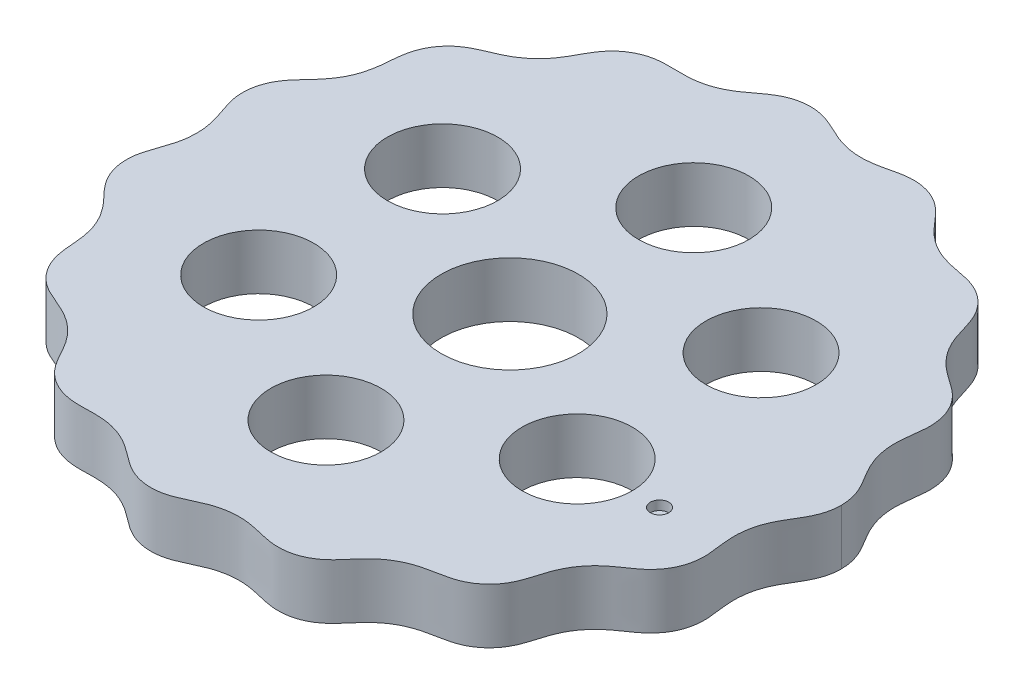
SolidWorks part; units mm, degrees
ref_plane "Front Plane" through (0, 0, 0) normal (0, 0, 1) x (1, 0, 0)
ref_plane "Top Plane" through (0, 0, 0) normal (0, 1, 0) x (1, 0, 0)
ref_plane "Right Plane" through (0, 0, 0) normal (1, 0, 0) x (0, 0, -1)
sketch "Sketch3" plane through (0, 0, 0) normal (0, 1, 0) x (1, 0, 0)
  line L0 (-55, 0) -> (55, 0) construction
  spline S0 degree 1 poles (-35.05, 0) (35.05, 0) knots 0 0 1 1 construction
  spline S1 degree 1 poles (-35.05, 0) (35.05, 0) knots 0 0 1 1 construction
  spline S2 degree 4 poles (-35, 0) (-35, -0.0358) (-35.0006, -0.1075) (-35.0034, -0.2568) (-35.0108, -0.4216) (-35.0218, -0.5882) (-35.0365, -0.7567) (-35.0593, -0.9658) (-35.104, -1.2906) (-35.1852, -1.7284) (-35.3211, -2.2743) (-35.5114, -2.8829) (-35.7441, -3.5419) (-35.9992, -4.258) (-36.256, -5.1614) (-36.3903, -6.2748) (-36.277, -7.5121) (-35.8687, -8.6952) (-35.2773, -9.6694) (-34.5543, -10.5199) (-33.7836, -11.2989) (-32.9858, -12.2016) (-32.2646, -13.303) (-31.7377, -14.5286) (-31.4262, -15.8454) (-31.2991, -17.2726) (-31.2161, -18.7053) (-30.8161, -20.1006) (-30.0732, -21.3418) (-29.1744, -22.2504) (-28.1724, -22.8961) (-27.1276, -23.3559) (-26.1086, -23.7587) (-25.0498, -24.278) (-23.9897, -24.9979) (-23.0387, -25.9222) (-22.2349, -27.0329) (-21.57, -28.2819) (-20.9001, -29.5134) (-19.9625, -30.5741) (-18.7952, -31.3663) (-17.5956, -31.8107) (-16.4147, -31.9743) (-15.2812, -31.959) (-14.2035, -31.9175) (-13.0422, -31.968) (-11.7833, -32.2012) (-10.5313, -32.6697) (-9.484, -33.2925) (-8.6483, -33.9206) (-7.824, -34.5602) (-6.9633, -35.1551) (-5.8447, -35.655) (-4.4715, -35.8938) (-3.1871, -35.8055) (-2.026, -35.4617) (-0.9923, -34.9762) (-0.0227, -34.5029) (1.0531, -34.0876) (2.2996, -33.7945) (3.6433, -33.7224) (5.0385, -33.8989) (6.246, -34.2125) (7.2644, -34.4441) (8.3052, -34.5433) (9.3521, -34.4822) (10.5168, -34.1673) (11.6593, -33.5372) (12.5907, -32.7091) (13.341, -31.8149) (14.0543, -30.9824) (14.885, -30.183) (15.9219, -29.4318) (16.9904, -28.9178) (18.0263, -28.6023) (18.918, -28.4136) (19.5788, -28.294) (20.4038, -28.1355) (21.3777, -27.8617) (22.444, -27.3351) (23.4837, -26.4602) (24.2541, -25.4059) (24.7506, -24.2626) (25.0639, -23.1466) (25.3786, -22.114) (25.8131, -21.0649) (26.4604, -19.9607) (27.3438, -18.9326) (28.3229, -18.1436) (29.2182, -17.5418) (30.0287, -16.9727) (30.7971, -16.3286) (31.5499, -15.4136) (32.138, -14.1887) (32.4089, -12.902) (32.389, -11.6377) (32.2136, -10.4744) (32.0853, -9.3852) (32.0701, -8.4106) (32.1519, -7.5639) (32.3146, -6.756) (32.5488, -5.9926) (32.8579, -5.2665) (33.2246, -4.5794) (33.5887, -3.9735) (33.9236, -3.4333) (34.2476, -2.8753) (34.5352, -2.2866) (34.722, -1.7814) (34.8335, -1.3753) (34.8947, -1.0872) (34.9248, -0.9216) (34.9499, -0.7552) (34.9676, -0.6083) (34.9796, -0.4838) (34.9875, -0.3802) (34.9925, -0.2949) (34.9973, -0.1832) (34.9994, -0.0895) (35, -0.0358) (35, 0) knots 0.07237 0.07237 0.07237 0.07237 0.07237 0.073615 0.074861 0.076106 0.077352 0.078597 0.079843 0.082334 0.087049 0.091763 0.096478 0.101193 0.107725 0.114257 0.124215 0.134174 0.144133 0.15093 0.157727 0.167143 0.176558 0.186521 0.196482 0.206428 0.216375 0.228908 0.238867 0.248826 0.258784 0.266347 0.27391 0.282559 0.291208 0.301173 0.311645 0.3216 0.331555 0.343059 0.353018 0.362977 0.372935 0.380513 0.388091 0.396475 0.404859 0.414823 0.425824 0.43578 0.440758 0.445737 0.45671 0.466668 0.476627 0.486585 0.494428 0.502271 0.510391 0.51851 0.528475 0.540003 0.54996 0.559918 0.565389 0.570861 0.580819 0.590778 0.600736 0.609095 0.617453 0.625308 0.633162 0.643126 0.655188 0.660155 0.665121 0.670088 0.675054 0.685012 0.69497 0.704929 0.714887 0.72326 0.731632 0.739222 0.746812 0.756777 0.769366 0.779036 0.78387 0.788705 0.798662 0.808621 0.81858 0.828538 0.837175 0.845812 0.853389 0.860965 0.865947 0.870929 0.877739 0.88455 0.889251 0.893953 0.898654 0.903356 0.908335 0.913314 0.914559 0.915803 0.917048 0.918293 0.919538 0.92016 0.920783 0.921405 0.922028 0.923272 0.923272 0.923272 0.923272 0.923272 construction
  spline S3 degree 4 poles (-35, 0) (-35, 0.0358) (-35.0006, 0.1075) (-35.0034, 0.2568) (-35.0108, 0.4216) (-35.0218, 0.5882) (-35.0365, 0.7567) (-35.0593, 0.9658) (-35.104, 1.2906) (-35.1852, 1.7284) (-35.3211, 2.2743) (-35.5114, 2.8829) (-35.7441, 3.5419) (-35.9992, 4.258) (-36.256, 5.1614) (-36.3903, 6.2748) (-36.277, 7.5121) (-35.8687, 8.6952) (-35.2773, 9.6694) (-34.5543, 10.5199) (-33.7836, 11.2989) (-32.9858, 12.2016) (-32.2646, 13.303) (-31.7377, 14.5286) (-31.4262, 15.8454) (-31.2991, 17.2726) (-31.2161, 18.7053) (-30.8161, 20.1006) (-30.0732, 21.3418) (-29.1744, 22.2504) (-28.1724, 22.8961) (-27.1276, 23.3559) (-26.1086, 23.7587) (-25.0498, 24.278) (-23.9897, 24.9979) (-23.0387, 25.9222) (-22.2349, 27.0329) (-21.57, 28.2819) (-20.9001, 29.5134) (-19.9625, 30.5741) (-18.7952, 31.3663) (-17.5956, 31.8107) (-16.4147, 31.9743) (-15.2812, 31.959) (-14.2035, 31.9175) (-13.0422, 31.968) (-11.7833, 32.2012) (-10.5313, 32.6697) (-9.484, 33.2925) (-8.6483, 33.9206) (-7.824, 34.5602) (-6.9633, 35.1551) (-5.8447, 35.655) (-4.4715, 35.8938) (-3.1871, 35.8055) (-2.026, 35.4617) (-0.9923, 34.9762) (-0.0227, 34.5029) (1.0531, 34.0876) (2.2996, 33.7945) (3.6433, 33.7224) (5.0385, 33.8989) (6.246, 34.2125) (7.2644, 34.4441) (8.3052, 34.5433) (9.3521, 34.4822) (10.5168, 34.1673) (11.6593, 33.5372) (12.5907, 32.7091) (13.341, 31.8149) (14.0543, 30.9824) (14.885, 30.183) (15.9219, 29.4318) (16.9904, 28.9178) (18.0263, 28.6023) (18.918, 28.4136) (19.5788, 28.294) (20.4038, 28.1355) (21.3777, 27.8617) (22.444, 27.3351) (23.4837, 26.4602) (24.2541, 25.4059) (24.7506, 24.2626) (25.0639, 23.1466) (25.3786, 22.114) (25.8131, 21.0649) (26.4604, 19.9607) (27.3438, 18.9326) (28.3229, 18.1436) (29.2182, 17.5418) (30.0287, 16.9727) (30.7971, 16.3286) (31.5499, 15.4136) (32.138, 14.1887) (32.4089, 12.902) (32.389, 11.6377) (32.2136, 10.4744) (32.0853, 9.3852) (32.0701, 8.4106) (32.1519, 7.5639) (32.3146, 6.756) (32.5488, 5.9926) (32.8579, 5.2665) (33.2246, 4.5794) (33.5887, 3.9735) (33.9236, 3.4333) (34.2476, 2.8753) (34.5352, 2.2866) (34.722, 1.7814) (34.8335, 1.3753) (34.8947, 1.0872) (34.9248, 0.9216) (34.9499, 0.7552) (34.9676, 0.6083) (34.9796, 0.4838) (34.9875, 0.3802) (34.9925, 0.2949) (34.9973, 0.1832) (34.9994, 0.0895) (35, 0.0358) (35, 0) knots 0.07237 0.07237 0.07237 0.07237 0.07237 0.073615 0.074861 0.076106 0.077352 0.078597 0.079843 0.082334 0.087049 0.091763 0.096478 0.101193 0.107725 0.114257 0.124215 0.134174 0.144133 0.15093 0.157727 0.167143 0.176558 0.186521 0.196482 0.206428 0.216375 0.228908 0.238867 0.248826 0.258784 0.266347 0.27391 0.282559 0.291208 0.301173 0.311645 0.3216 0.331555 0.343059 0.353018 0.362977 0.372935 0.380513 0.388091 0.396475 0.404859 0.414823 0.425824 0.43578 0.440758 0.445737 0.45671 0.466668 0.476627 0.486585 0.494428 0.502271 0.510391 0.51851 0.528475 0.540003 0.54996 0.559918 0.565389 0.570861 0.580819 0.590778 0.600736 0.609095 0.617453 0.625308 0.633162 0.643126 0.655188 0.660155 0.665121 0.670088 0.675054 0.685012 0.69497 0.704929 0.714887 0.72326 0.731632 0.739222 0.746812 0.756777 0.769366 0.779036 0.78387 0.788705 0.798662 0.808621 0.81858 0.828538 0.837175 0.845812 0.853389 0.860965 0.865947 0.870929 0.877739 0.88455 0.889251 0.893953 0.898654 0.903356 0.908335 0.913314 0.914559 0.915803 0.917048 0.918293 0.919538 0.92016 0.920783 0.921405 0.922028 0.923272 0.923272 0.923272 0.923272 0.923272 construction
  spline S4 degree 3 poles (-35.05, 0) (-35.05, 0.5942) (-35.1913, 1.7871) (-35.7746, 3.4796) (-36.3707, 5.1933) (-36.4396, 7.0303) (-35.9255, 8.7962) (-34.8763, 10.2953) (-33.5855, 11.5493) (-32.4877, 12.9692) (-31.743, 14.607) (-31.3966, 16.3685) (-31.3265, 18.1656) (-30.9526, 19.9545) (-30.0177, 21.5385) (-28.6321, 22.7475) (-26.9685, 23.4758) (-24.7571, 24.3804) (-22.9113, 25.9836) (-21.7349, 28.0635) (-20.8793, 29.6605) (-19.5893, 30.9697) (-17.9506, 31.8041) (-16.1382, 32.0667) (-14.3404, 31.9481) (-12.5497, 32.0566) (-10.8259, 32.5717) (-9.2705, 33.4703) (-7.8874, 34.6161) (-6.3279, 35.5665) (-4.5333, 35.9699) (-2.7029, 35.7895) (-1.0358, 35.0637) (0.5722, 34.2737) (2.3132, 33.8221) (4.1122, 33.7899) (5.8663, 34.152) (7.6191, 34.6038) (9.4554, 34.5619) (11.1856, 33.9386) (12.6201, 32.7974) (13.7402, 31.3837) (15.0004, 30.1082) (16.5216, 29.1475) (18.2225, 28.5672) (19.9964, 28.2983) (22.3428, 27.6504) (24.2012, 25.897) (25.0056, 23.6053) (25.4804, 21.8775) (26.285, 20.2693) (27.4434, 18.8926) (28.8726, 17.8119) (30.3879, 16.8259) (31.6155, 15.4611) (32.3458, 13.7735) (32.4979, 11.9454) (32.205, 10.1635) (32.0758, 8.3758) (32.3517, 6.5979) (33.0336, 4.9347) (34.012, 3.4312) (34.8553, 1.8179) (35.05, 0.6019) (35.05, 0) knots 0.07237 0.07237 0.07237 0.07237 0.085665 0.09896 0.112256 0.125551 0.138846 0.152142 0.165437 0.178732 0.192028 0.205323 0.218619 0.231914 0.245209 0.258505 0.2718 0.285095 0.311686 0.324981 0.338277 0.351572 0.364867 0.378163 0.391458 0.404754 0.418049 0.431344 0.44464 0.457935 0.47123 0.484526 0.497821 0.511116 0.524412 0.537707 0.551002 0.564298 0.577593 0.590889 0.604184 0.617479 0.630775 0.64407 0.657365 0.670661 0.683956 0.710547 0.723842 0.737137 0.750433 0.763728 0.777024 0.790319 0.803614 0.81691 0.830205 0.8435 0.856796 0.870091 0.883386 0.896682 0.909977 0.923272 0.923272 0.923272 0.923272
  spline S5 degree 3 poles (35.05, 0) (35.05, -0.6019) (34.8553, -1.8179) (34.012, -3.4312) (33.0336, -4.9347) (32.3517, -6.5979) (32.0758, -8.3758) (32.205, -10.1635) (32.4979, -11.9454) (32.3458, -13.7735) (31.6155, -15.4611) (30.3879, -16.8259) (28.8726, -17.8119) (27.4434, -18.8926) (26.285, -20.2693) (25.4804, -21.8775) (25.0056, -23.6053) (24.2012, -25.897) (22.3428, -27.6504) (19.9964, -28.2983) (18.2225, -28.5672) (16.5216, -29.1475) (15.0004, -30.1082) (13.7402, -31.3837) (12.6201, -32.7974) (11.1856, -33.9386) (9.4554, -34.5619) (7.6191, -34.6038) (5.8663, -34.152) (4.1122, -33.7899) (2.3132, -33.8221) (0.5722, -34.2737) (-1.0358, -35.0637) (-2.7029, -35.7895) (-4.5333, -35.9699) (-6.3279, -35.5665) (-7.8874, -34.6161) (-9.2705, -33.4703) (-10.8259, -32.5717) (-12.5497, -32.0566) (-14.3404, -31.9481) (-16.1382, -32.0667) (-17.9506, -31.8041) (-19.5893, -30.9697) (-20.8793, -29.6605) (-21.7349, -28.0635) (-22.9113, -25.9836) (-24.7571, -24.3804) (-26.9685, -23.4758) (-28.6321, -22.7475) (-30.0177, -21.5385) (-30.9526, -19.9545) (-31.3265, -18.1656) (-31.3966, -16.3685) (-31.743, -14.607) (-32.4877, -12.9692) (-33.5855, -11.5493) (-34.8763, -10.2953) (-35.9255, -8.7962) (-36.4396, -7.0303) (-36.3707, -5.1933) (-35.7746, -3.4796) (-35.1913, -1.7871) (-35.05, -0.5942) (-35.05, 0) knots 0.07237 0.07237 0.07237 0.07237 0.085665 0.09896 0.112256 0.125551 0.138846 0.152142 0.165437 0.178732 0.192028 0.205323 0.218619 0.231914 0.245209 0.258505 0.2718 0.285095 0.311686 0.324981 0.338277 0.351572 0.364867 0.378163 0.391458 0.404754 0.418049 0.431344 0.44464 0.457935 0.47123 0.484526 0.497821 0.511116 0.524412 0.537707 0.551002 0.564298 0.577593 0.590889 0.604184 0.617479 0.630775 0.64407 0.657365 0.670661 0.683956 0.710547 0.723842 0.737137 0.750433 0.763728 0.777024 0.790319 0.803614 0.81691 0.830205 0.8435 0.856796 0.870091 0.883386 0.896682 0.909977 0.923272 0.923272 0.923272 0.923272
  dimension "D1" = 0.05
extrude "Boss-Extrude1" add sketch "Sketch3" along normal blind 6
sketch "Sketch4" plane through (0, 6, 0) normal (0, 1, 0) x (1, 0, 0)
  circle A0 centre (-1, 0) radius 7.475
  circle A1 centre (-1, 0) radius 20 construction
  circle A2 centre (-1, 20) radius 6
  circle A3 centre (16.3205, 10) radius 6
  circle A4 centre (16.3205, -10) radius 6
  circle A5 centre (-1, -20) radius 6
  circle A6 centre (-18.3205, -10) radius 6
  circle A7 centre (-18.3205, 10) radius 6
  point P19 (-1, 0)
  dimension "D1" = 14.95
  dimension "D2" = 40
  dimension "D3" = 12
  dimension "D5" = 1
  dimension "D4" = 6
extrude "Cut-Extrude1" cut sketch "Sketch4" against normal through all
sketch "Sketch5" plane through (0, 6, 0) normal (0, 1, 0) x (1, 0, 0)
  circle A0 centre (25.3715, -10.0924) radius 1
  dimension "D1" = 2
extrude "Cut-Extrude2" cut sketch "Sketch5" against normal blind 1 contours A0
equation "\"R_SUN\"= 40"
equation "\"R_ROLL\"= 5"
equation "\"GRATIO\"= 15"
equation "\"RHO\"= 1"
